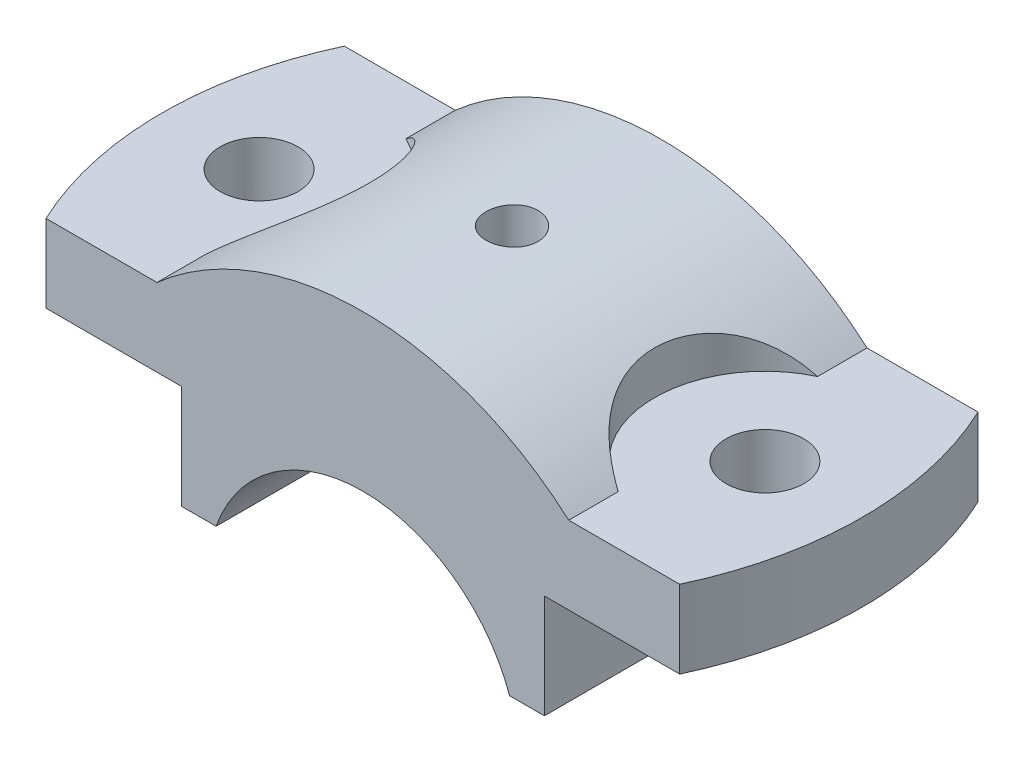
SolidWorks part; units mm, degrees
ref_plane "Front Plane" through (0, 0, 0) normal (0, 0, 1) x (1, 0, 0)
ref_plane "Top Plane" through (0, 0, 0) normal (0, 1, 0) x (1, 0, 0)
ref_plane "Right Plane" through (0, 0, 0) normal (1, 0, 0) x (0, 0, -1)
sketch "Sketch1" plane through (0, 0, 0) normal (0, 0, 1) x (1, 0, 0)
  line L0 (22.6274, 0) -> (28, 0)
  line L1 (28, 0) -> (28, 16)
  line L2 (28, 16) -> (54, 16)
  line L3 (54, 16) -> (54, 28)
  line L4 (54, 28) -> (31.749, 28)
  line L5 (0, 0) -> (0, 16) construction
  line L6 (-54, 16.0058) -> (-54, 28)
  line L7 (-54, 28) -> (-31.749, 28)
  line L8 (-28, 16.0058) -> (-54, 16.0058)
  line L9 (-22.6274, 0) -> (-28, 0)
  line L10 (-28, 0) -> (-28, 16.0058)
  arc A0 (-22.6274, 0) -> (22.6274, 0) centre (0, -8) cw
  arc A1 (-31.749, 28) -> (31.749, 28) centre (0, -8) cw
  point P6 (0, 40)
  point P15 (-28, 8.0029)
  point P20 (0, 16)
  dimension "D1" = 24
  dimension "D2" = 48
  dimension "D7" = 8
  dimension "D3" = 12
  dimension "D4" = 16
  dimension "D5" = 56
  dimension "D6" = 108
  dimension "D8" = 54
  dimension "D9" = 8.0029
extrude "Boss-Extrude1" add sketch "Sketch1" along normal blind 46
ref_plane "Plane2" through (0, 28, 0) normal (0, 1, 0) x (1, 0, 0)
sketch "Sketch2" plane through (0, 28, 0) normal (0, 1, 0) x (1, 0, 0)
  line L0 (0, 0) -> (0, -46) construction
  line L1 (-31.749, -46) -> (31.749, -46) construction
  line L2 (-54, -23) -> (54, -23) construction
  line L3 (-54, -46) -> (-54, 0) construction
  line L4 (54, -46) -> (54, 0) construction
  line L6 (54, -46) -> (31.749, -46) construction
  line L7 (54, 0) -> (31.749, 0) construction
  line L8 (48.8569, 0) -> (54, 0)
  line L9 (54, 0) -> (54, -46)
  line L10 (54, -46) -> (48.8569, -46)
  line L11 (-48.8569, 0) -> (-54, 0)
  line L12 (-54, 0) -> (-54, -46)
  line L13 (-54, -46) -> (-48.8569, -46)
  arc A0 (48.8569, 0) -> (48.8569, -46) centre (0, -23) cw
  arc A1 (-48.8569, 0) -> (-48.8569, -46) centre (0, -23) ccw
  dimension "D1" = 54
extrude "Cut-Extrude1" cut sketch "Sketch2" against normal through all contours L9 A0 L10 | L8 A0 L9 | A1 L11 L12 | A1 L12 L13
sketch "Sketch3" plane through (0, 28, 0) normal (0, 1, 0) x (1, 0, 0)
  line L0 (0, 0) -> (0, -46) construction
  line L1 (-31.749, -46) -> (31.749, -46) construction
  line L2 (-54, -23) -> (54, -23) construction
  arc A0 (-48.8569, 0) -> (-48.8569, -46) centre (0, -23) ccw construction
  arc A1 (48.8569, -46) -> (48.8569, 0) centre (0, -23) ccw construction
  circle A2 centre (39, -23) radius 6
  circle A3 centre (-39, -23) radius 6
  dimension "D1" = 12
  dimension "D2" = 39
extrude "Cut-Extrude2" cut sketch "Sketch3" against normal through all
ref_plane "Plane3" through (0, 40, 0) normal (0, 1, 0) x (1, 0, 0)
sketch "Sketch5" plane through (0, 40, 0) normal (0, 1, 0) x (1, 0, 0)
  line L0 (0, 0) -> (0, -46) construction
  line L1 (-31.749, -46) -> (31.749, -46) construction
  circle A0 centre (0, -23) radius 3
  dimension "D1" = 6
extrude "Cut-Extrude3" cut sketch "Sketch5" against normal through all
sketch "Sketch6" plane through (0, 40, 0) normal (0, 1, 0) x (1, 0, 0)
  circle A0 centre (0, -23) radius 4
  dimension "D1" = 8
extrude "Cut-Extrude4" cut sketch "Sketch6" against normal blind 16
ref_plane "Plane4" through (0, 0, 23) normal (0, 0, 1) x (1, 0, 0)
ref_plane "Plane5" through (0, 28, 0) normal (0, 1, 0) x (1, 0, 0)
sketch "Sketch7" plane through (0, 28, 0) normal (0, 1, 0) x (1, 0, 0)
  line L0 (39, -17) -> (39, -29)
  line L1 (31.749, -46) -> (31.749, 0) construction
  line L2 (31.749, -38.3761) -> (31.749, -7.6239)
  line L3 (0, 0) -> (0, 10.3538)
  line L4 (-31.749, -38.3761) -> (-31.749, -7.6239)
  circle A0 centre (39, -23) radius 6 construction
  arc A1 (31.749, -7.6239) -> (31.749, -38.3761) centre (39, -23) ccw
  arc A2 (-31.749, -7.6239) -> (-31.749, -38.3761) centre (-39, -23) cw
  dimension "D1" = 17
extrude "Cut-Extrude5" cut sketch "Sketch7" along normal through all contours A2 L4 | L2 A1
